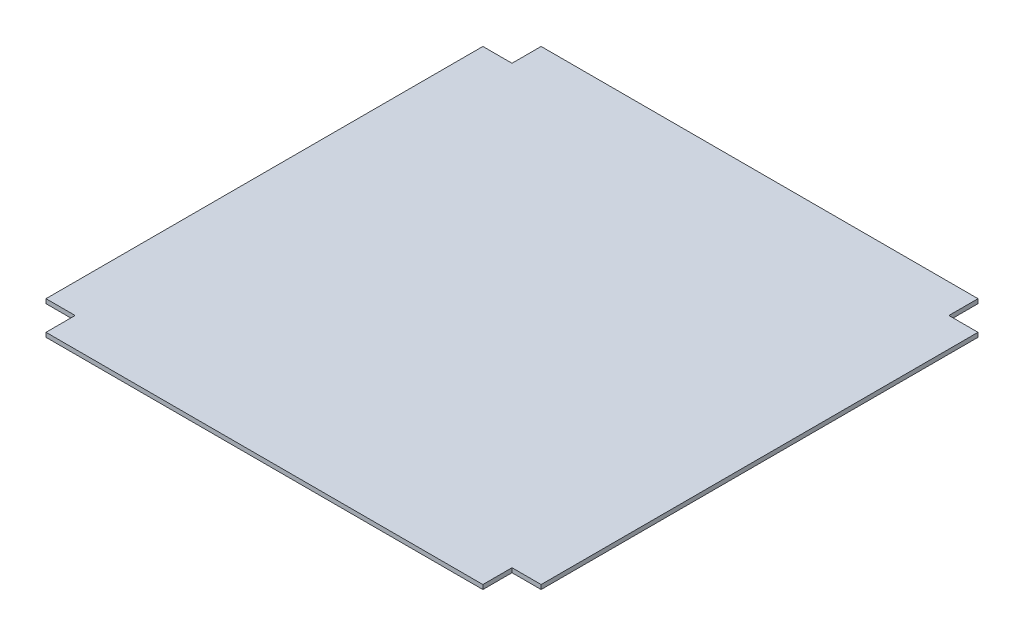
SolidWorks part; units mm, degrees
ref_plane "Front Plane" through (0, 0, 0) normal (0, 0, 1) x (1, 0, 0)
ref_plane "Top Plane" through (0, 0, 0) normal (0, 1, 0) x (1, 0, 0)
ref_plane "Right Plane" through (0, 0, 0) normal (1, 0, 0) x (0, 0, -1)
sketch "Sketch1" plane through (0, 0, 0) normal (0, 1, 0) x (1, 0, 0)
  line L0 (0, 170) -> (41.5119, 170) construction
  line L1 (0, 0) -> (340, 0)
  line L2 (0, 0) -> (0, 340)
  line L3 (0, 340) -> (340, 340)
  line L4 (340, 0) -> (340, 340)
  line L5 (0, 340) -> (20, 340)
  line L6 (0, 340) -> (0, 320)
  line L7 (0, 320) -> (20, 320)
  line L8 (20, 340) -> (20, 320)
  line L9 (340, 340) -> (320, 340)
  line L10 (340, 340) -> (340, 320)
  line L11 (340, 320) -> (320, 320)
  line L12 (320, 340) -> (320, 320)
  line L13 (320, 0) -> (320, 20)
  line L14 (340, 20) -> (320, 20)
  line L15 (340, 0) -> (340, 20)
  line L16 (340, 0) -> (320, 0)
  line L17 (20, 0) -> (20, 20)
  line L18 (0, 20) -> (20, 20)
  line L19 (0, 0) -> (0, 20)
  line L20 (0, 0) -> (20, 0)
  line L21 (0, 0) -> (340, 0)
  dimension "D1" = 340
  dimension "D2" = 340
  dimension "D3" = 20
  dimension "D4" = 20
  dimension "D5" = 20
  dimension "D6" = 20
extrude "Boss-Extrude1" add sketch "Sketch1" along normal blind 3
